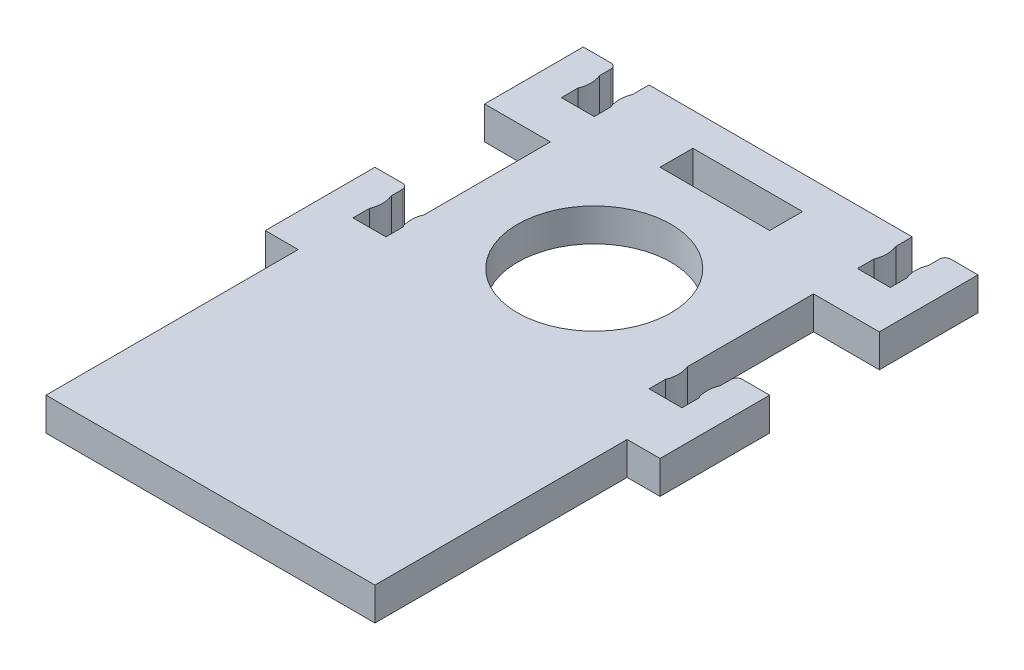
SolidWorks part; units mm, degrees
ref_plane "Front Plane" through (0, 0, 0) normal (0, 0, 1) x (1, 0, 0)
ref_plane "Top Plane" through (0, 0, 0) normal (0, 1, 0) x (1, 0, 0)
ref_plane "Right Plane" through (0, 0, 0) normal (1, 0, 0) x (0, 0, -1)
sketch "Sketch1" plane through (0, 0, 0) normal (0, 1, 0) x (1, 0, 0)
  line L0 (-23.1986, -13) -> (6.8014, -13)
  line L1 (6.8014, -13) -> (6.8014, 10)
  line L2 (6.8014, 10) -> (9.8014, 10)
  line L3 (9.8014, 10) -> (9.8014, 20)
  line L4 (9.8014, 20) -> (6.8014, 20)
  line L5 (6.8014, 20) -> (6.8014, 18.5)
  line L6 (6.8014, 15) -> (3.8014, 15)
  line L7 (3.8014, 16.5) -> (3.8014, 15)
  line L8 (3.8014, 30) -> (9.8014, 30)
  line L9 (9.8014, 30) -> (9.8014, 39)
  line L10 (9.8014, 39) -> (6.8014, 39)
  line L11 (6.8014, 39) -> (6.8014, 37.5)
  line L12 (6.8014, 34) -> (3.8014, 34)
  line L13 (3.8014, 34) -> (3.8014, 35.5)
  line L14 (3.8014, 39) -> (-20.1986, 39)
  line L15 (-8.1986, 33) -> (-8.1986, 41.1142) construction
  line L16 (-20.1986, 35.5) -> (-20.1986, 34)
  line L17 (-23.1986, 34) -> (-20.1986, 34)
  line L18 (-23.1986, 39) -> (-23.1986, 37.5)
  line L19 (-26.1986, 39) -> (-23.1986, 39)
  line L20 (-26.1986, 30) -> (-26.1986, 39)
  line L21 (-20.1986, 30) -> (-26.1986, 30)
  line L22 (-26.1986, 20) -> (-23.1986, 20)
  line L23 (-23.1986, 20) -> (-23.1986, 18.5)
  line L24 (-23.1986, 15) -> (-20.1986, 15)
  line L25 (-20.1986, 15) -> (-20.1986, 16.5)
  line L26 (-23.1986, 10) -> (-26.1986, 10)
  line L27 (-26.1986, 10) -> (-26.1986, 20)
  line L28 (-23.1986, 10) -> (-23.1986, -13)
  line L29 (6.6014, 38.8859) -> (6.6014, 34.4662) construction
  line L30 (-13.1986, 36) -> (-3.1986, 36)
  line L31 (-13.1986, 36) -> (-13.1986, 33)
  line L32 (-13.1986, 33) -> (-3.1986, 33)
  line L33 (-3.1986, 36) -> (-3.1986, 33)
  line L34 (5.8631, 37.5) -> (7.9279, 37.5) construction
  line L35 (5.8631, 35.5) -> (7.9279, 35.5) construction
  line L36 (5.3014, 34) -> (5.3014, 39) construction
  line L37 (6.8014, 16.5) -> (6.8014, 15)
  line L38 (-20.1986, 37.5) -> (-20.1986, 39)
  line L39 (-23.1986, 35.5) -> (-23.1986, 34)
  line L40 (-23.1986, 16.5) -> (-23.1986, 15)
  line L41 (6.8014, 35.5) -> (6.8014, 34)
  line L42 (3.8014, 37.5) -> (3.8014, 39)
  line L43 (3.8014, 18.5) -> (3.8014, 30)
  line L44 (-20.1986, 18.5) -> (-20.1986, 30)
  circle A0 centre (-8.1986, 22) radius 7
  arc A1 (6.8014, 35.5) -> (6.8014, 37.5) centre (9.2014, 36.5) cw
  arc A2 (3.8014, 35.5) -> (3.8014, 37.5) centre (1.4014, 36.5) ccw
  arc A3 (6.8014, 18.5) -> (6.8014, 16.5) centre (9.2014, 17.5) ccw
  arc A4 (3.8014, 18.5) -> (3.8014, 16.5) centre (1.4014, 17.5) cw
  arc A5 (-20.1986, 35.5) -> (-20.1986, 37.5) centre (-17.7986, 36.5) cw
  arc A6 (-23.1986, 35.5) -> (-23.1986, 37.5) centre (-25.5986, 36.5) ccw
  arc A7 (-20.1986, 18.5) -> (-20.1986, 16.5) centre (-17.7986, 17.5) ccw
  arc A8 (-23.1986, 18.5) -> (-23.1986, 16.5) centre (-25.5986, 17.5) cw
  dimension "D21" = 14
  dimension "D23" = 17
  dimension "D2" = 30
  dimension "D3" = 10
  dimension "D4" = 23
  dimension "D5" = 3
  dimension "D6" = 5
  dimension "D7" = 3
  dimension "D8" = 15
  dimension "D9" = 6
  dimension "D10" = 9
  dimension "D11" = 3
  dimension "D12" = 5
  dimension "D13" = 3
  dimension "D14" = 5
  dimension "D15" = 3
  dimension "D16" = 24
  dimension "D17" = 3
  dimension "D18" = 3
  dimension "D20" = 10
  dimension "D24" = 52
  dimension "D25" = 5
  dimension "D27" = 1.5
  dimension "D28" = 1.5
extrude "Boss-Extrude1" add sketch "Sketch1" along normal blind 3
fillet "Fillet1" radius 0.5 4 edges at (-23.1986, 1.5, -20) (-23.1986, 1.5, -39) (6.8014, 1.5, -20) (6.8014, 1.5, -39)
